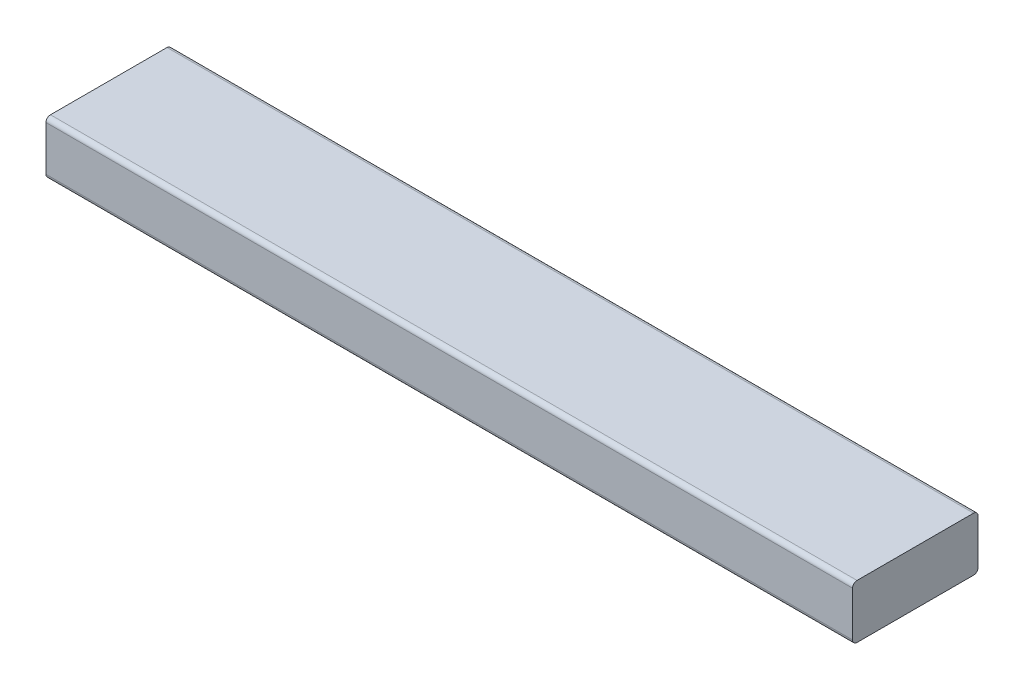
SolidWorks part; units mm, degrees
material "Pine"
ref_plane "Front Plane" through (0, 0, 0) normal (0, 0, 1) x (1, 0, 0)
ref_plane "Top Plane" through (0, 0, 0) normal (0, 1, 0) x (1, 0, 0)
ref_plane "Right Plane" through (0, 0, 0) normal (1, 0, 0) x (0, 0, -1)
sketch "Sketch1" plane through (0, 0, 0) normal (0, 0, 1) x (1, 0, 0)
  line L1 (-285.75, 38.1) -> (285.75, 38.1)
  line L2 (-285.75, 38.1) -> (-285.75, 0)
  line L3 (-285.75, 0) -> (285.75, 0)
  line L4 (285.75, 38.1) -> (285.75, 0)
  point P4 (0, 0)
  dimension "D1" = 571.5
  dimension "D2" = 38.1
extrude "Boss-Extrude1" add sketch "Sketch1" along normal blind 88.9
fillet "Fillet1" radius 3.175 4 edges at (0, 0, 0) (0, 0, 88.9) (0, 38.1, 0) (0, 38.1, 88.9)
